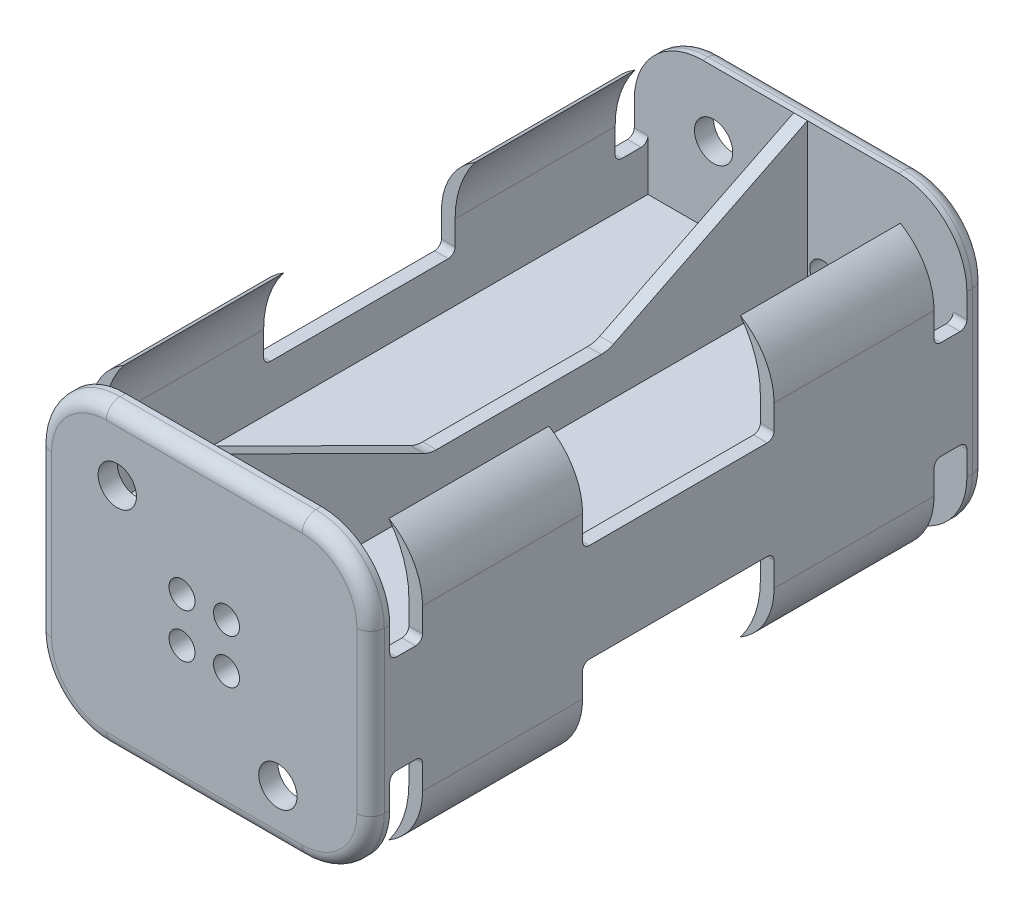
SolidWorks part; units mm, degrees
ref_plane "Front Plane" through (0, 0, 0) normal (0, 0, 1) x (1, 0, 0)
ref_plane "Top Plane" through (0, 0, 0) normal (0, 1, 0) x (1, 0, 0)
ref_plane "Right Plane" through (0, 0, 0) normal (1, 0, 0) x (0, 0, -1)
sketch "Sketch1" plane through (0, 0, 0) normal (0, 0, 1) x (1, 0, 0)
  line L0 (1.2123, 1.2123) -> (2.9186, 2.9186) construction
  line L1 (-9.0932, 13.8049) -> (9.0932, 13.8049)
  line L2 (-15.4432, 7.4549) -> (-15.4432, -7.4549)
  line L3 (-9.0932, -13.8049) -> (9.0932, -13.8049)
  line L4 (15.4432, 7.4549) -> (15.4432, -7.4549)
  line L5 (-15.4432, 13.8049) -> (15.4432, -13.8049) construction
  line L6 (-15.4432, -13.8049) -> (15.4432, 13.8049) construction
  line L11 (-1.8777, 1.6785) -> (1.8777, -1.6785) construction
  line L12 (-1.4964, -1.4964) -> (2.0655, 2.0655) construction
  line L13 (-1.2123, 1.2123) -> (1.2123, -1.2123) construction
  line L14 (-1.2123, -1.2123) -> (1.2123, 1.2123) construction
  arc A0 (9.0932, 13.8049) -> (15.4432, 7.4549) centre (9.0932, 7.4549) cw
  arc A1 (9.0932, -13.8049) -> (15.4432, -7.4549) centre (9.0932, -7.4549) ccw
  arc A2 (-15.4432, -7.4549) -> (-9.0932, -13.8049) centre (-9.0932, -7.4549) ccw
  arc A3 (-9.0932, 13.8049) -> (-15.4432, 7.4549) centre (-9.0932, 7.4549) ccw
  circle A4 centre (-8.0772, 7.7851) radius 1.778
  circle A5 centre (6.8344, -8.8961) radius 1.778
  circle A6 centre (2.0655, 2.0655) radius 1.2065
  circle A7 centre (2.0655, -2.0655) radius 1.2065
  circle A8 centre (-2.0655, -2.0655) radius 1.2065
  circle A9 centre (-2.0655, 2.0655) radius 1.2065
  point P0 (0, 0)
  point P20 (-6.7104, 6.6479)
  point P21 (6.4129, -5.3482)
  point P24 (-8.0772, 6.0071)
  point P25 (-9.8552, 7.7851)
  point P26 (0, 0)
  point P28 (0, 0)
  dimension "D3" = 6.35
  dimension "D4" = 6.35
  dimension "D5" = 3.556
  dimension "D6" = 2.413
  dimension "D1" = 30.8864
  dimension "D2" = 27.6098
  dimension "D7" = 19.812
  dimension "D8" = 5.588
  dimension "D9" = 3.429
  dimension "D11" = 2.0655
  dimension "D12" = 2.0655
  dimension "D10" = 4
extrude "Boss-Extrude1" add sketch "Sketch1" along normal blind 57.15
ref_plane "Plane1" through (0, 0, 1.778) normal (0, 0, -1) x (-1, 0, 0)
sketch "Sketch2" plane through (0, 0, 1.778) normal (0, 0, -1) x (-1, 0, 0)
  line L0 (-12.3159, 12.9264) -> (-12.3159, 13.8049)
  line L1 (-14.1732, 0.4699) -> (-0.635, 0.4699)
  line L2 (-14.1732, 7.4549) -> (-14.1732, -7.4549)
  line L3 (-14.1732, 7.4549) -> (-14.1732, 0.4699)
  line L4 (-9.0932, 13.8049) -> (9.0932, 13.8049) construction
  line L5 (-0.635, 0.4699) -> (-0.635, 13.8049)
  line L6 (0, 13.8049) -> (0, -13.8049) construction
  line L7 (9.0932, -13.8049) -> (-9.0932, -13.8049) construction
  line L8 (-15.4432, 0) -> (15.4432, 0) construction
  line L9 (-15.4432, -7.4549) -> (-15.4432, 7.4549) construction
  line L10 (15.4432, 7.4549) -> (15.4432, -7.4549) construction
  line L11 (-12.3159, 13.8049) -> (-0.635, 13.8049)
  line L12 (14.1732, 0.4699) -> (0.635, 0.4699)
  line L13 (14.1732, 7.4549) -> (14.1732, 0.4699)
  line L14 (12.3159, 12.9264) -> (12.3159, 13.8049)
  line L15 (0.635, 0.4699) -> (0.635, 13.8049)
  line L16 (-14.1732, -7.4549) -> (-14.1732, -0.4699)
  line L17 (-14.1732, -0.4699) -> (-0.635, -0.4699)
  line L18 (14.1732, -0.4699) -> (0.635, -0.4699)
  line L19 (14.1732, -7.4549) -> (14.1732, -0.4699)
  line L20 (12.3159, 13.8049) -> (0.635, 13.8049)
  line L21 (-12.3159, -12.9264) -> (-12.3159, -13.8049)
  line L22 (0.635, -0.4699) -> (0.635, -13.8049)
  line L23 (-0.635, -0.4699) -> (-0.635, -13.8049)
  line L24 (-12.3159, -13.8049) -> (-0.635, -13.8049)
  line L25 (12.3159, -13.8049) -> (0.635, -13.8049)
  line L26 (12.3159, -12.9264) -> (12.3159, -13.8049)
  arc A1 (-14.1732, 7.4549) -> (-12.3159, 12.9264) centre (-5.1854, 7.4549) cw
  arc A2 (-9.0932, 12.5349) -> (-14.1732, 7.4549) centre (-9.0932, 7.4549) ccw
  arc A3 (14.1732, 7.4549) -> (12.3159, 12.9264) centre (5.1854, 7.4549) ccw
  arc A4 (-14.1732, -7.4549) -> (-12.3159, -12.9264) centre (-5.1854, -7.4549) ccw
  arc A5 (14.1732, -7.4549) -> (12.3159, -12.9264) centre (5.1854, -7.4549) cw
  arc A6 (-9.0932, 13.8049) -> (-15.4432, 7.4549) centre (-9.0932, 7.4549) ccw construction
  dimension "D2" = 13.335
  dimension "D3" = 0.635
  dimension "D4" = 11.6809
  dimension "D1" = 1.27
extrude "Cut-Extrude1" cut sketch "Sketch2" against normal offset from surface (53.594 mm away) 1.778 up to face at (-0.859, -2.0655, 57.15)
sketch "Sketch3" plane through (-15.4432, 0, 0) normal (-1, 0, 0) x (0, 0, 1)
  line L0 (0, 0) -> (57.15, 0) construction
  line L1 (57.15, 7.4549) -> (57.15, -7.4549) construction
  line L2 (1.778, 12.9264) -> (1.778, 5.207)
  line L3 (1.778, 13.7884) -> (1.778, -13.7884) construction
  line L4 (2.413, 4.572) -> (4.191, 4.572)
  line L5 (4.826, 5.207) -> (4.826, 12.9264)
  line L6 (55.372, 12.9264) -> (1.778, 12.9264) construction
  line L7 (4.826, 12.9264) -> (1.778, 12.9264)
  line L8 (28.575, 12.9264) -> (28.575, -13.8049) construction
  line L9 (55.372, -13.8049) -> (1.778, -13.8049) construction
  line L10 (54.737, 4.572) -> (52.959, 4.572)
  line L11 (55.372, 12.9264) -> (55.372, 5.207)
  line L12 (52.324, 12.9264) -> (55.372, 12.9264)
  line L13 (52.324, 5.207) -> (52.324, 12.9264)
  line L14 (2.413, -4.572) -> (4.191, -4.572)
  line L15 (1.778, -12.9264) -> (1.778, -5.207)
  line L16 (4.826, -12.9264) -> (1.778, -12.9264)
  line L17 (4.826, -5.207) -> (4.826, -12.9264)
  line L18 (54.737, -4.572) -> (52.959, -4.572)
  line L19 (52.324, -12.9264) -> (55.372, -12.9264)
  line L20 (55.372, -12.9264) -> (55.372, -5.207)
  line L21 (52.324, -5.207) -> (52.324, -12.9264)
  line L22 (19.685, -4.572) -> (37.465, -12.9264) construction
  line L23 (19.685, 12.9264) -> (37.465, 12.9264)
  line L24 (19.685, 12.9264) -> (19.685, 5.207)
  line L25 (20.32, 4.572) -> (36.83, 4.572)
  line L26 (37.465, 12.9264) -> (37.465, 5.207)
  line L27 (19.685, 12.9264) -> (37.465, 4.572) construction
  line L28 (19.685, 4.572) -> (37.465, 12.9264) construction
  line L29 (19.685, -12.9264) -> (37.465, -4.572) construction
  line L30 (37.465, -12.9264) -> (37.465, -5.207)
  line L31 (20.32, -4.572) -> (36.83, -4.572)
  line L32 (19.685, -12.9264) -> (19.685, -5.207)
  line L33 (19.685, -12.9264) -> (37.465, -12.9264)
  arc A0 (1.778, 5.207) -> (2.413, 4.572) centre (2.413, 5.207) ccw
  arc A1 (4.191, 4.572) -> (4.826, 5.207) centre (4.191, 5.207) ccw
  arc A2 (2.413, -4.572) -> (1.778, -5.207) centre (2.413, -5.207) ccw
  arc A3 (4.191, -4.572) -> (4.826, -5.207) centre (4.191, -5.207) cw
  arc A4 (54.737, -4.572) -> (55.372, -5.207) centre (54.737, -5.207) cw
  arc A5 (52.959, -4.572) -> (52.324, -5.207) centre (52.959, -5.207) ccw
  arc A6 (52.959, 4.572) -> (52.324, 5.207) centre (52.959, 5.207) cw
  arc A7 (54.737, 4.572) -> (55.372, 5.207) centre (54.737, 5.207) ccw
  arc A8 (19.685, 5.207) -> (20.32, 4.572) centre (20.32, 5.207) ccw
  arc A9 (36.83, 4.572) -> (37.465, 5.207) centre (36.83, 5.207) ccw
  arc A10 (36.83, -4.572) -> (37.465, -5.207) centre (36.83, -5.207) cw
  arc A11 (19.685, -5.207) -> (20.32, -4.572) centre (20.32, -5.207) cw
  point P13 (28.575, 0)
  point P32 (1.778, 4.572)
  point P35 (4.826, 4.572)
  point P38 (1.778, -4.572)
  point P41 (4.826, -4.572)
  point P44 (55.372, -4.572)
  point P47 (52.324, -4.572)
  point P50 (52.324, 4.572)
  point P53 (55.372, 4.572)
  point P54 (28.575, 8.7492)
  point P75 (28.575, -8.7492)
  dimension "D3" = 0.635
  dimension "D4" = 0.635
  dimension "D6" = 0.635
  dimension "D1" = 4.572
  dimension "D2" = 3.048
  dimension "D5" = 17.78
extrude "Cut-Extrude2" cut sketch "Sketch3" against normal blind 8.128
mirror "Mirror1" about plane through (0, 0, 0) normal (1, 0, 0) of "Cut-Extrude2"
fillet "Fillet2" radius 1.27 8 edges at (-15.4432, 0, 57.15) (0, -13.8049, 57.15) (15.4432, 0, 57.15) (0, 13.8049, 57.15) (-13.5833, 11.945, 57.15) (-13.5833, -11.945, 57.15) (13.5833, -11.945, 57.15) (13.5833, 11.945, 57.15)
fillet "Fillet3" radius 1.27 8 edges at (0, -13.8049, 0) (-13.5833, -11.945, 0) (-15.4432, 0, 0) (-13.5833, 11.945, 0) (13.5833, -11.945, 0) (15.4432, 0, 0) (13.5833, 11.945, 0) (0, 13.8049, 0)
sketch "Sketch4" plane through (0.635, 0, 0) normal (1, 0, 0) x (0, 0, -1)
  line L0 (-20.32, 4.572) -> (-36.83, 4.572) construction
  line L1 (-20.9174, 4.572) -> (-36.2326, 4.572)
  line L2 (-55.372, 13.8049) -> (-1.778, 13.8049) construction
  line L3 (-55.372, 13.8049) -> (-1.778, 13.8049)
  line L4 (-55.372, 13.8049) -> (-37.3648, 4.8383)
  line L5 (-19.7852, 4.8383) -> (-1.778, 13.8049)
  line L6 (0, 0) -> (-57.15, 0) construction
  line L7 (-57.15, -7.4549) -> (-57.15, 7.4549) construction
  line L8 (-55.372, -13.8049) -> (-1.778, -13.8049)
  line L9 (-19.7852, -4.8383) -> (-1.778, -13.8049)
  line L10 (-20.9174, -4.572) -> (-36.2326, -4.572)
  line L11 (-55.372, -13.8049) -> (-37.3648, -4.8383)
  arc A0 (-36.2326, 4.572) -> (-37.3648, 4.8383) centre (-36.2326, 7.112) cw
  arc A1 (-20.9174, 4.572) -> (-19.7852, 4.8383) centre (-20.9174, 7.112) ccw
  arc A2 (-20.9174, -4.572) -> (-19.7852, -4.8383) centre (-20.9174, -7.112) cw
  arc A3 (-36.2326, -4.572) -> (-37.3648, -4.8383) centre (-36.2326, -7.112) ccw
  dimension "D1" = 2.54
  dimension "D2" = 2.54
extrude "Cut-Extrude3" cut sketch "Sketch4" against normal blind 3.048
